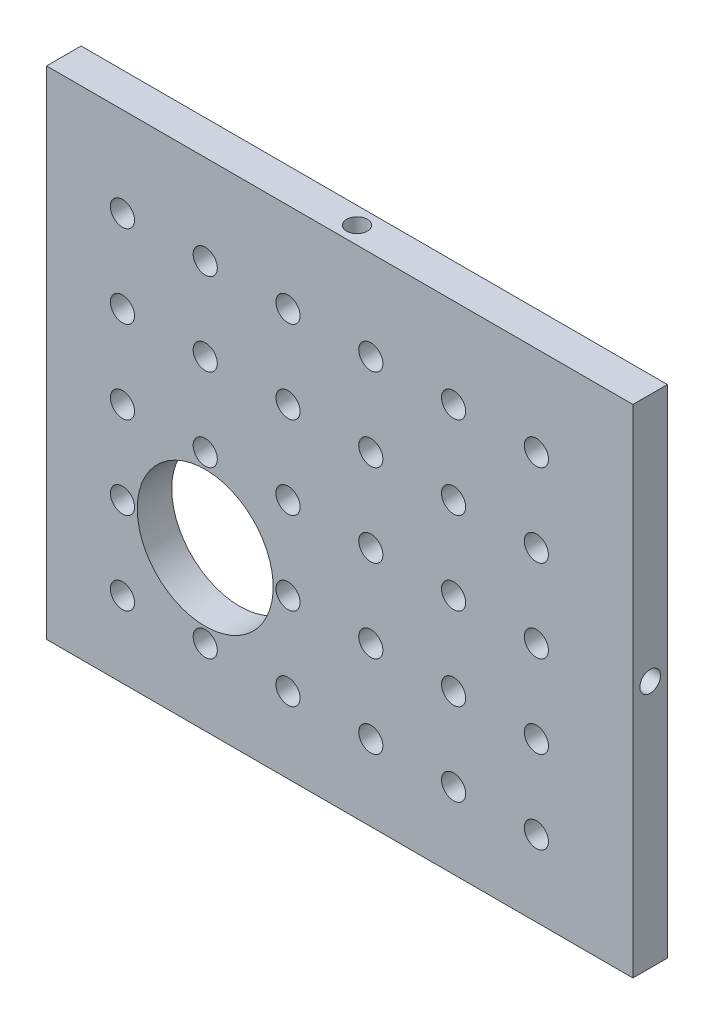
SolidWorks part; units mm, degrees
ref_plane "Plan de face" through (0, 0, 0) normal (0, 0, 1) x (1, 0, 0)
ref_plane "Plan de dessus" through (0, 0, 0) normal (0, 1, 0) x (1, 0, 0)
ref_plane "Plan de droite" through (0, 0, 0) normal (1, 0, 0) x (0, 0, -1)
sketch "Esquisse1" plane through (0, 0, 0) normal (0, 0, 1) x (1, 0, 0)
  line L1 (-42.5, -36) -> (42.5, -36)
  line L2 (-42.5, -36) -> (-42.5, 36)
  line L3 (-42.5, 36) -> (42.5, 36)
  line L4 (42.5, -36) -> (42.5, 36)
  line L5 (-42.5, -36) -> (42.5, 36) construction
  line L6 (-42.5, 36) -> (42.5, -36) construction
  point P0 (0, 0)
  dimension "D1" = 72
  dimension "D2" = 85
extrude "Boss.-Extru.1" add sketch "Esquisse1" along normal blind 5
sketch "Esquisse3" plane through (-42.5, 0, 0) normal (-1, 0, 0) x (0, 0, 1)
  line L0 (-8.5295, 0) -> (13.5295, 0) construction
  line L1 (2.5, 36) -> (2.5, -37.4544) construction
  line L2 (5, 36) -> (0, 36) construction
  circle A0 centre (2.5, 0) radius 1.5
  dimension "D1" = 3
extrude "Enlèv. mat.-Extru.5" cut sketch "Esquisse3" against normal blind 5
mirror "Symétrie1" about plane through (0, 0, 0) normal (1, 0, 0) of "Enlèv. mat.-Extru.5"
sketch "Esquisse5" plane through (0, 0, 0) normal (0, 0, 1) x (1, 0, 0)
  line L0 (-42.5, -36) -> (42.5, -36) construction
  line L2 (-42.5, 36) -> (-42.5, -36) construction
  circle A0 centre (-31.5, -25) radius 1.75
  dimension "D1" = 3.5
  dimension "D2" = 11
  dimension "D3" = 11
extrude "Enlèv. mat.-Extru.6" cut sketch "Esquisse5" along normal up to surface (5 mm away) up to face at (0, 0, 5)
pattern_linear "Répétition linéaire2" count 6 spacing 12 along (1, 0, 0) count 5 spacing 12 along (0, 1, 0) of "Enlèv. mat.-Extru.6"
sketch "Esquisse6" plane through (0, 0, 0) normal (0, 0, 1) x (1, 0, 0)
  circle A2 centre (-19.5, -13) radius 9.8523
  dimension "D1" = 19.7047
extrude "Enlèv. mat.-Extru.7" cut sketch "Esquisse6" along normal up to surface (5 mm away) up to face at (-21.25, -25, 5)
sketch "Esquisse8" plane through (0, 36, 0) normal (0, 1, 0) x (1, 0, 0)
  line L0 (-42.5, -2.5) -> (46.7621, -2.5) construction
  line L1 (-42.5, -5) -> (-42.5, 0) construction
  line L2 (0, 7.2443) -> (0, -9.709) construction
  circle A0 centre (0, -2.5) radius 1.5
  dimension "D1" = 3
extrude "Enlèv. mat.-Extru.8" cut sketch "Esquisse8" against normal blind 5
mirror "Symétrie2" about plane through (0, 0, 0) normal (0, 1, 0) of "Enlèv. mat.-Extru.8"
sketch "Esquisse10" [suppressed] plane through (0, 0, 6) normal (0, 0, 1) x (1, 0, 0)
  line L1 (35.9, -26.2) -> (42.5, -26.2)
  line L2 (35.9, -26.2) -> (35.9, -12.6)
  line L3 (35.9, -12.6) -> (42.5, -12.6)
  line L4 (42.5, -26.2) -> (42.5, -12.6)
  line L5 (35.9, -26.2) -> (42.5, -12.6) construction
  line L6 (35.9, -12.6) -> (42.5, -26.2) construction
  line L7 (-42.5, -35) -> (42.5, -35) construction
  line L8 (42.5, -35) -> (42.5, 35) construction
  point P0 (39.2, -19.4)
  dimension "D1" = 13.6
  dimension "D2" = 6.6
  dimension "D4" = 8.8
extrude "Enlèv. mat.-Extru.10" [suppressed] cut sketch "Esquisse10" against normal up to surface (6 mm away)
